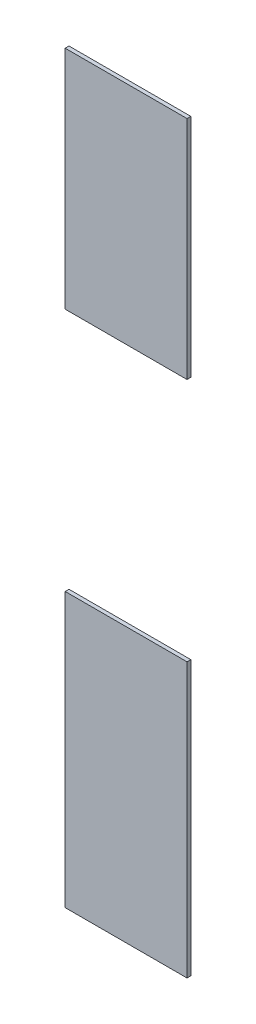
SolidWorks part; units mm, degrees
material "Гипс"
ref_plane "Спереди" through (0, 0, 0) normal (0, 0, 1) x (1, 0, 0)
ref_plane "Сверху" through (0, 0, 0) normal (0, 1, 0) x (1, 0, 0)
ref_plane "Справа" through (0, 0, 0) normal (1, 0, 0) x (0, 0, -1)
sketch "Эскиз1" plane through (0, 0, 0) normal (0, 0, 1) x (1, 0, 0)
  line L0 (800, -1545) -> (0, -1545) construction
  line L1 (0, 0) -> (400, 0)
  line L2 (0, 0) -> (0, -742.25)
  line L3 (0, -742.25) -> (400, -742.25)
  line L4 (400, 0) -> (400, -742.25)
  line L5 (0, -2444.25) -> (400, -2444.25)
  line L6 (0, -2444.25) -> (0, -1545)
  line L7 (0, -1545) -> (400, -1545)
  line L8 (400, -2444.25) -> (400, -1545)
extrude "Бобышка-Вытянуть1" add sketch "Эскиз1" along normal blind 12.5
